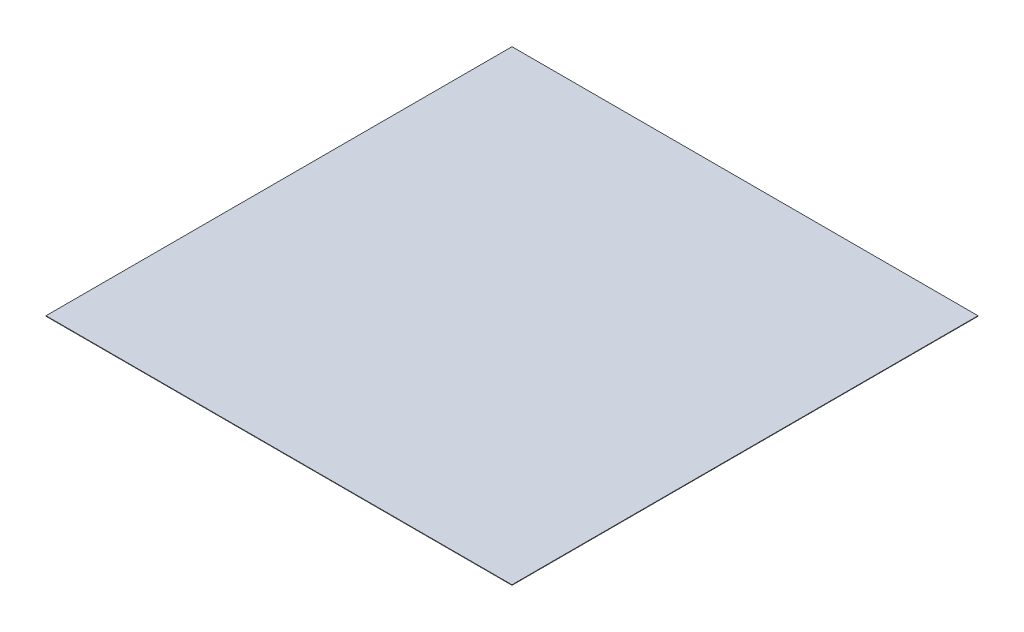
SolidWorks part; units mm, degrees
ref_plane "Front Plane" through (0, 0, 0) normal (0, 0, 1) x (1, 0, 0)
ref_plane "Top Plane" through (0, 0, 0) normal (0, 1, 0) x (1, 0, 0)
ref_plane "Right Plane" through (0, 0, 0) normal (1, 0, 0) x (0, 0, -1)
sketch "Sketch1" plane through (0, 0, 0) normal (0, 1, 0) x (1, 0, 0)
  line L1 (-620, -620) -> (620, -620)
  line L2 (-620, -620) -> (-620, 620)
  line L3 (-620, 620) -> (620, 620)
  line L4 (620, -620) -> (620, 620)
  line L5 (-620, -620) -> (620, 620) construction
  line L6 (-620, 620) -> (620, -620) construction
  point P0 (0, 0)
  dimension "D1" = 1240
  dimension "D2" = 1240
  dimension "D3" = 620
extrude "Boss-Extrude1" add sketch "Sketch1" along normal blind 1.27
